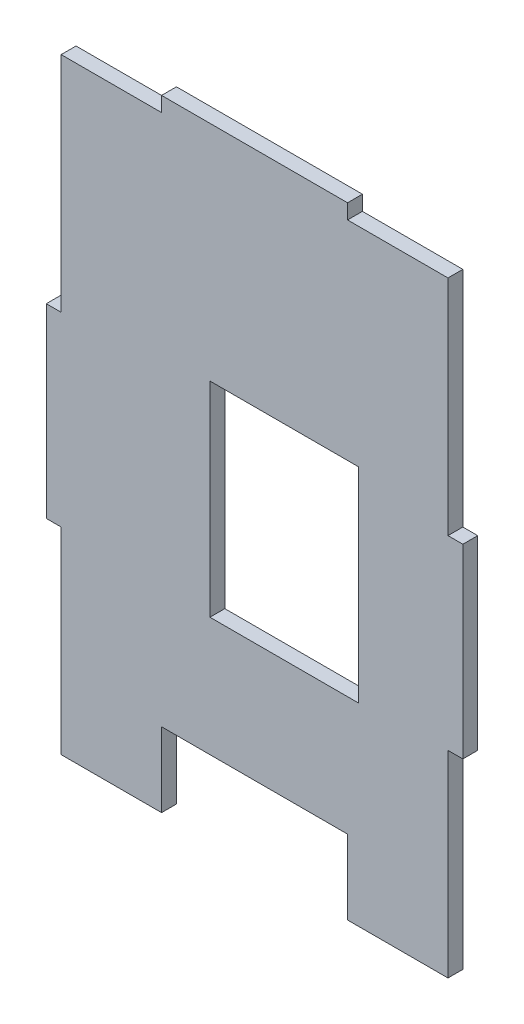
SolidWorks part; units mm, degrees
ref_plane "정면" through (0, 0, 0) normal (0, 0, 1) x (1, 0, 0)
ref_plane "윗면" through (0, 0, 0) normal (0, 1, 0) x (1, 0, 0)
ref_plane "우측면" through (0, 0, 0) normal (1, 0, 0) x (0, 0, -1)
sketch "스케치2" plane through (0, 0, 0) normal (0, 0, 1) x (1, 0, 0)
  line L1 (0, 87) -> (112, 87)
  line L2 (0, 87) -> (0, -85)
  line L3 (0, -85) -> (112, -85)
  line L4 (112, 87) -> (112, -85)
extrude "보스-돌출1" add sketch "스케치2" against normal blind 4
sketch "스케치3" plane through (0, 0, 0) normal (0, 0, 1) x (1, 0, 0)
  line L1 (112, 87) -> (108, 87)
  line L2 (112, 87) -> (112, 23)
  line L3 (112, 23) -> (108, 23)
  line L4 (108, 87) -> (108, 23)
  line L5 (108, -27) -> (112, -27)
  line L6 (108, -27) -> (108, -85)
  line L7 (108, -85) -> (112, -85)
  line L8 (112, -27) -> (112, -85)
  line L9 (0, 87) -> (4, 87)
  line L10 (0, 87) -> (0, 23)
  line L11 (0, 23) -> (4, 23)
  line L12 (4, 87) -> (4, 23)
  line L13 (4, -27) -> (0, -27)
  line L14 (4, -27) -> (4, -85)
  line L15 (4, -85) -> (0, -85)
  line L16 (0, -27) -> (0, -85)
  line L22 (108, 87) -> (81, 87)
  line L24 (108, 83) -> (81, 83)
  line L25 (81, 87) -> (81, 83)
  line L26 (4, 87) -> (31, 87)
  line L28 (4, 83) -> (31, 83)
  line L29 (31, 87) -> (31, 83)
  line M1 (0, 87) -> (0, -85)
  line M2 (0, -85) -> (112, -85)
  line M3 (112, -85) -> (112, 87)
  line M4 (112, 87) -> (0, 87)
  dimension "D1" = 27
  dimension "D2" = 4
  dimension "D3" = 4
  dimension "D4" = 27
extrude "컷-돌출2" cut sketch "스케치3" against normal blind 4 contours L25 L24 L4 M4 | L4 L3 M4 M3 | L29 L12 L28 M4 | L12 L11 M4 M1 | L14 L13 M1 M2 | L6 L7 L8 L5
sketch "스케치5" plane through (0, 0, 0) normal (0, 0, 1) x (1, 0, 0)
  line L0 (4, -27) -> (4, -85) construction
  line L1 (108, -85) -> (4, -85)
  line L2 (108, -85) -> (108, -80)
  line L3 (108, -80) -> (4, -80)
  line L4 (4, -85) -> (4, -80)
  dimension "D1" = 5
extrude "컷-돌출4" cut sketch "스케치5" against normal blind 4
sketch "스케치6" plane through (0, 0, 0) normal (0, 0, 1) x (1, 0, 0)
  line L0 (81, 87) -> (31, 87) construction
  line L1 (44, 27) -> (84, 27)
  line L2 (44, 27) -> (44, -28)
  line L3 (44, -28) -> (84, -28)
  line L4 (84, 27) -> (84, -28)
  line L5 (112, -27) -> (112, 23) construction
  dimension "D1" = 60
  dimension "D2" = 55
  dimension "D3" = 40
  dimension "D4" = 28
extrude "컷-돌출5" cut sketch "스케치6" against normal blind 4
sketch "스케치8" plane through (0, 0, 0) normal (0, 0, 1) x (1, 0, 0)
  line L0 (108, -80) -> (4, -80) construction
  line L1 (81, -80) -> (31, -80)
  line L2 (81, -80) -> (81, -60)
  line L3 (81, -60) -> (31, -60)
  line L4 (31, -80) -> (31, -60)
  line L5 (108, -27) -> (108, -80) construction
  dimension "D1" = 20
  dimension "D2" = 50
  dimension "D3" = 27
extrude "컷-돌출6" cut sketch "스케치8" against normal blind 4
